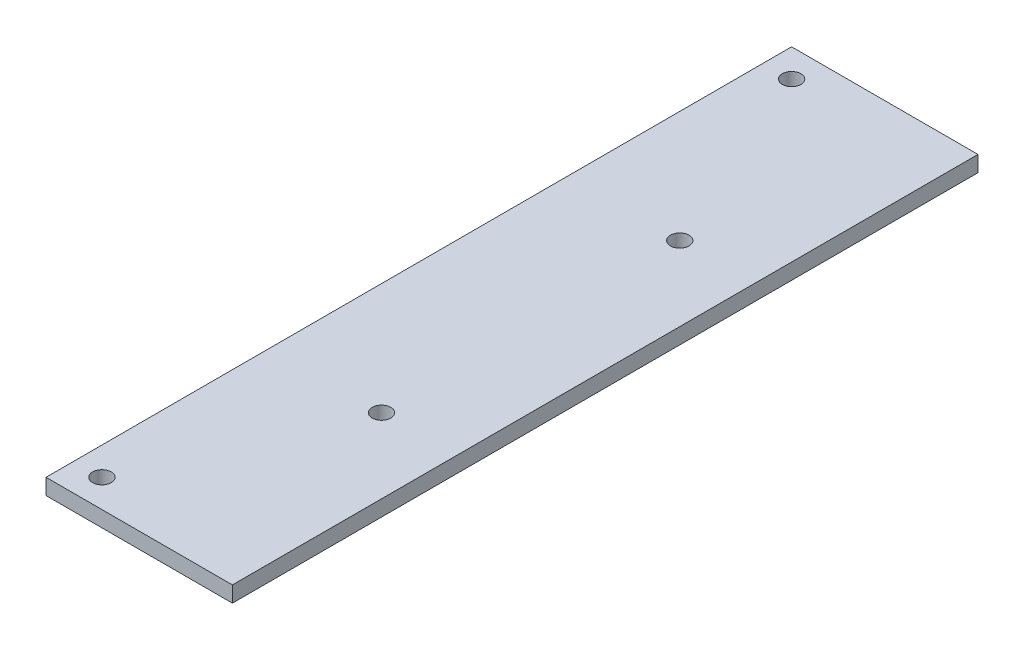
SolidWorks part; units mm, degrees
ref_plane "前视基准面" through (0, 0, 0) normal (0, 0, 1) x (1, 0, 0)
ref_plane "上视基准面" through (0, 0, 0) normal (0, 1, 0) x (1, 0, 0)
ref_plane "右视基准面" through (0, 0, 0) normal (1, 0, 0) x (0, 0, -1)
other "Configuration Table"
sketch "草图1" plane through (0, 0, 0) normal (0, 1, 0) x (1, 0, 0)
  line L22 (-10, -40) -> (10, -40)
  line L23 (-10, -40) -> (-10, 40)
  line L28 (-10, 40) -> (10, 40)
  line L29 (10, -40) -> (10, 40)
  line L37 (-10, -40) -> (10, 40) construction
  line L38 (-10, 40) -> (10, -40) construction
  circle A1 centre (2, 16) radius 1
  circle A2 centre (2, -16) radius 1
  circle A3 centre (-7, 37) radius 1
  circle A4 centre (-7, -37) radius 1
  point P0 (0, 0)
  point P15 (0, 0)
  dimension "D3" = 2
  dimension "D9" = 24
  dimension "D1" = 20
  dimension "D2" = 80
  dimension "D4" = 3
  dimension "D5" = 3
  dimension "D6" = 3
  dimension "D7" = 3
  dimension "D8" = 12
  dimension "D10" = 12
  dimension "D11" = 24
extrude "凸台-拉伸1" add sketch "草图1" along normal blind 1.7
sketch "草图3" plane through (0, 0, 0) normal (0, -1, 0) x (1, 0, 0)
  line L6 (-10, -40) -> (-10, 40) construction
  line L7 (-10, 5.6) -> (-4.6, 5.6)
  line L8 (-10, 5.6) -> (-10, -5.6)
  line L9 (-10, -5.6) -> (-4.6, -5.6)
  line L10 (-4.6, 5.6) -> (-4.6, -5.6)
  line L11 (0, 0) -> (-4.6, 0) construction
  dimension "D3" = 5.4
  dimension "D4" = 11.2
extrude "凸台-拉伸2" add sketch "草图3" along normal blind 2
